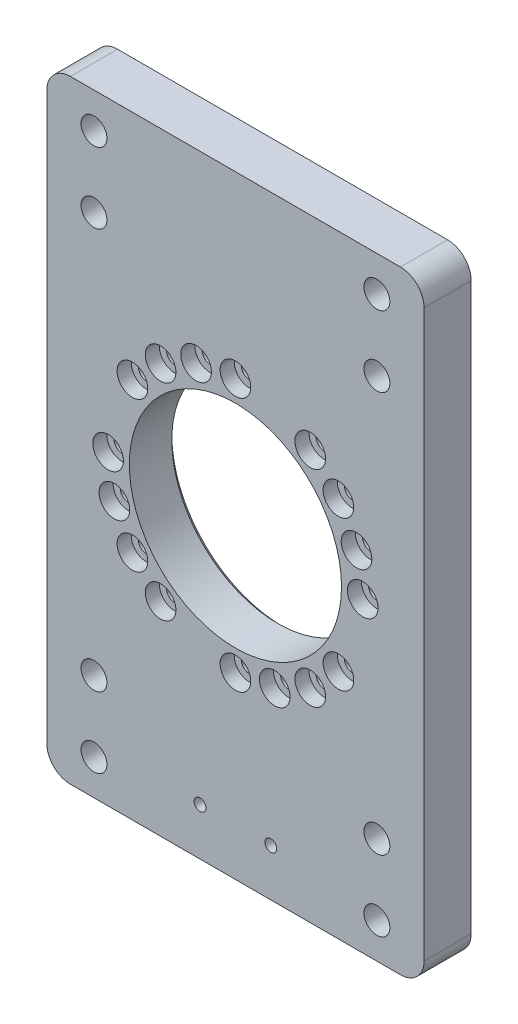
SolidWorks part; units mm, degrees
material "ALUMINIUM,  6082-T6"
ref_plane "Front Plane" through (0, 0, 0) normal (0, 0, 1) x (1, 0, 0)
ref_plane "Top Plane" through (0, 0, 0) normal (0, 1, 0) x (1, 0, 0)
ref_plane "Right Plane" through (0, 0, 0) normal (1, 0, 0) x (0, 0, -1)
sketch "Sketch1" plane through (0, 0, 0) normal (0, 0, 1) x (1, 0, 0)
  line L0 (40, 65) -> (-40, -65) construction
  line L1 (-40, 65) -> (40, 65)
  line L2 (-40, 65) -> (-40, -65)
  line L3 (-40, -65) -> (40, -65)
  line L4 (40, 65) -> (40, -65)
  circle A0 centre (0, 0) radius 22.5
  dimension "D1" = 45
  dimension "D2" = 80
  dimension "D3" = 130
extrude "Boss-Extrude1" add sketch "Sketch1" along normal blind 10
hole_wizard "CBORE for M3 Hex Socket Head Cap Screw1" positions "Sketch11" profile "Sketch3" counterbore size "M3" standard "ISO" end condition through all
sketch "Sketch11" plane through (0, 0, 10) normal (0, 0, 1) x (1, 0, 0)
  line L47 (-27, 0) -> (27, 0) construction
  line L52 (0, 27) -> (0, -27) construction
  line L54 (-25.6785, -8.3435) -> (25.6785, 8.3435) construction
  line L57 (21.8435, 15.8702) -> (-21.8435, -15.8702) construction
  line L60 (-15.8702, -21.8435) -> (15.8702, 21.8435) construction
  line L62 (-8.3435, 25.6785) -> (8.3435, -25.6785) construction
  line L65 (-15.8702, 21.8435) -> (15.8702, -21.8435) construction
  line L68 (-21.8435, 15.8702) -> (21.8435, -15.8702) construction
  circle A2 centre (0, 0) radius 27 construction
  circle A3 centre (0, 0) radius 22.5 construction
  point P157 (-27, 0)
  point P164 (-25.6785, -8.3435)
  point P166 (-21.8435, -15.8702)
  point P168 (-15.8702, -21.8435)
  point P170 (27, 0)
  point P172 (25.6785, 8.3435)
  point P174 (21.8435, 15.8702)
  point P176 (15.8702, 21.8435)
  point P178 (0, 27)
  point P180 (-8.3435, 25.6785)
  point P184 (-15.8702, 21.8435)
  point P186 (-21.8435, 15.8702)
  point P188 (0, -27)
  point P190 (8.3435, -25.6785)
  point P192 (15.8702, -21.8435)
  point P194 (21.8435, -15.8702)
  dimension "D1" = 54
  dimension "D2" = 18
  dimension "D3" = 18
  dimension "D4" = 18
  dimension "D5" = 18
  dimension "D6" = 18
  dimension "D7" = 18
sketch "Sketch3" plane through (-27, 0, 10) normal (1, 0, 0) x (0, -1, 0)
  line L0 (0, 0) -> (0, 10)
  line L1 (0, 10) -> (1.75, 10)
  line L3 (1.75, 10) -> (1.75, 3)
  line L4 (1.75, 3) -> (3.25, 3)
  line L5 (3.25, 3) -> (3.25, 0)
  line L7 (3.25, 0) -> (0, 0)
  line L11 (0, -6.35) -> (0, 107.95) construction
  dimension "Thru Hole Dia." = 3.5
  dimension "Thru Hole Depth" = 10
  dimension "C'Bore Dia." = 6.5
  dimension "C'Bore Depth" = 3
chamfer "Chamfer1" distance 1 angle 45 1 edges at (22.5, 0, 0)
hole_wizard "Ø5.5 (5.5) Diameter Hole1" positions "Sketch7" profile "Sketch8" hole size "Ø5.5" standard "ISO" end condition through all
sketch "Sketch7" plane through (0, 0, 10) normal (0, 0, 1) x (1, 0, 0)
  line L1 (-30, 57.5) -> (-30, -57.5) construction
  line L3 (-30, -57.5) -> (30, -57.5) construction
  line L5 (30, -57.5) -> (30, 57.5) construction
  line L7 (30, 57.5) -> (-30, 57.5) construction
  line L15 (-30, 57.5) -> (30, -57.5) construction
  line L17 (40, 65) -> (-40, 65) construction
  line L18 (-30, -42.5) -> (30, -42.5) construction
  line L21 (30, 42.5) -> (-30, 42.5) construction
  line L23 (-30, -42.5) -> (30, 42.5) construction
  point P0 (-30, 57.5)
  point P4 (30, 57.5)
  point P10 (30, -57.5)
  point P14 (-30, -57.5)
  point P71 (-30, -42.5)
  point P74 (-30, 42.5)
  point P77 (30, 42.5)
  point P80 (30, -42.5)
  dimension "D1" = 15
  dimension "D2" = 7.5
  dimension "D3" = 30
  dimension "D4" = 85
sketch "Sketch8" plane through (-30, 57.5, 10) normal (1, 0, 0) x (0, -1, 0)
  line L0 (0, 0) -> (0, 10)
  line L1 (0, 10) -> (2.75, 10)
  line L2 (2.75, 10) -> (2.75, 0)
  line L5 (2.75, 0) -> (0, 0)
  line L11 (0, -6.35) -> (0, 107.95) construction
  dimension "Thru Hole Dia." = 5.5
  dimension "Thru Hole Depth" = 10
fillet "Fillet1" radius 5 4 edges at (-40, 65, 5) (40, 65, 5) (40, -65, 5) (-40, -65, 5)
hole_wizard "M3 Tapped Hole1" positions "Sketch9" profile "Sketch10" tap size "M3" standard "ISO" end condition through all
sketch "Sketch9" plane through (0, 0, 0) normal (0, 0, -1) x (-1, 0, 0)
  line L0 (-7.5, -55) -> (7.5, -55) construction
  line L3 (0, -55) -> (0, 0) construction
  line L5 (35, -65) -> (-35, -65) construction
  point P0 (-7.5, -55)
  point P2 (7.5, -55)
  dimension "D1" = 15
  dimension "D2" = 10
sketch "Sketch10" plane through (7.5, -55, 0) normal (1, 0, 0) x (0, 1, 0)
  line L0 (0, 0) -> (0, 10)
  line L1 (0, 10) -> (1.25, 10)
  line L2 (1.25, 10) -> (1.25, 0)
  line L5 (1.25, 0) -> (0, 0)
  line L11 (0, -6.35) -> (0, 107.95) construction
  dimension "Thru Tap Drill Dia." = 2.5
  dimension "Thru Tap Drill Depth" = 10
cosmetic thread "Hole Thread1" parameters "D2"=3
cosmetic thread "Hole Thread2" parameters "D2"=3
